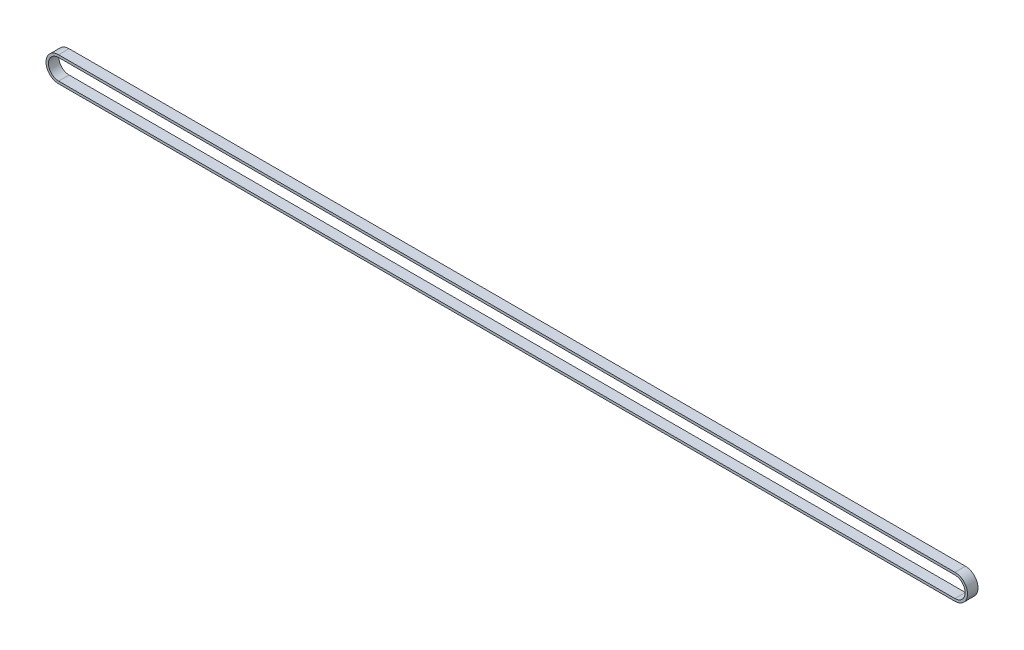
SolidWorks part; units mm, degrees
material "BUTYL"
ref_plane "Front Plane" through (0, 0, 0) normal (0, 0, 1) x (1, 0, 0)
ref_plane "Top Plane" through (0, 0, 0) normal (0, 1, 0) x (1, 0, 0)
ref_plane "Right Plane" through (0, 0, 0) normal (1, 0, 0) x (0, 0, -1)
sketch "Sketch1" plane through (0, 0, 0) normal (0, 0, 1) x (1, 0, 0)
  line L0 (0, 0) -> (513, 0) construction
  line L1 (0, 7.213) -> (513, 7.213)
  line L2 (0, -7.213) -> (513, -7.213)
  line L3 (0, 5.833) -> (513, 5.833)
  line L4 (513, -5.833) -> (0, -5.833)
  arc A0 (0, 7.213) -> (0, -7.213) centre (0, 0) ccw
  arc A1 (513, -7.213) -> (513, 7.213) centre (513, 0) ccw
  arc A2 (0, 5.833) -> (0, -5.833) centre (0, 0) ccw
  arc A3 (513, -5.833) -> (513, 5.833) centre (513, 0) ccw
  dimension "D2" = 1.38
  dimension "D3" = 7.213
  dimension "D1" = 513
extrude "Boss-Extrude1" add sketch "Sketch1" along normal blind 6
